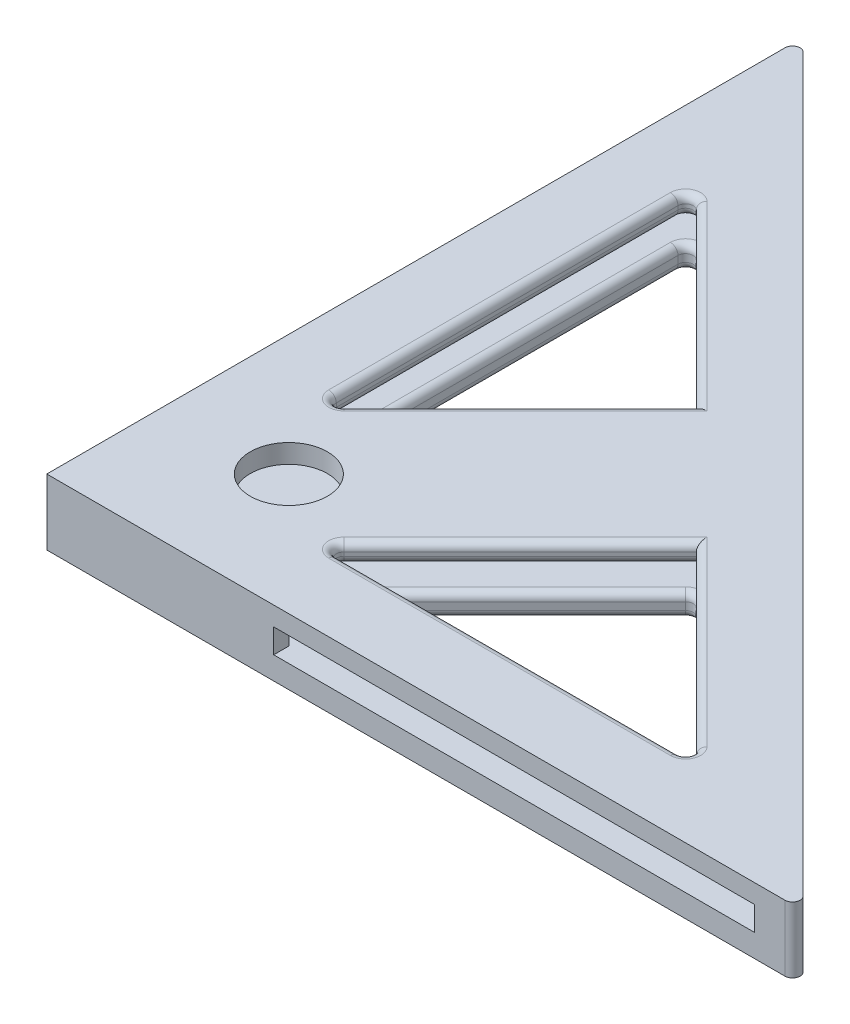
SolidWorks part; units mm, degrees
ref_plane "Front Plane" through (0, 0, 0) normal (0, 0, 1) x (1, 0, 0)
ref_plane "Top Plane" through (0, 0, 0) normal (0, 1, 0) x (1, 0, 0)
ref_plane "Right Plane" through (0, 0, 0) normal (1, 0, 0) x (0, 0, -1)
sketch "Sketch1" plane through (0, 0, 0) normal (0, 1, 0) x (1, 0, 0)
  line L0 (0, 0) -> (0, 28)
  line L1 (0, 28) -> (28, 0)
  line L2 (28, 0) -> (0, 0)
  circle A0 centre (14, 14) radius 5.1
  circle A1 centre (14, 14) radius 6.6
  dimension "D1" = 14
  dimension "D3" = 10.2
  dimension "D4" = 13.2
  dimension "D2" = 14
extrude "Boss-Extrude1" add sketch "Sketch1" along normal blind 3.1 contours L1 A1 A0 | L1 A1 A0
sketch "Sketch2" plane through (0, 3.1, 0) normal (0, 1, 0) x (1, 0, 0)
  line L0 (0, 0) -> (0, 28)
  line L1 (0, 28) -> (28, 0)
  line L2 (28, 0) -> (0, 0)
  line L3 (0, 28) -> (16.8443, 19.9557)
  line L4 (28, 0) -> (19.9557, 16.8443)
  line L5 (21.4946, 8.981) -> (23.8734, 4)
  line L6 (23.8734, 4) -> (18.6188, 4)
  line L7 (18.6188, 4) -> (21.4946, 8.981)
  line L8 (0, 0) -> (18.6669, 18.6669) construction
  line L9 (4, 23.8734) -> (4, 18.6188)
  line L10 (8.981, 21.4946) -> (4, 23.8734)
  line L11 (4, 18.6188) -> (8.981, 21.4946)
  circle A0 centre (14, 14) radius 6.6
  circle M11 centre (14, 14) radius 5.1
  circle M12 centre (14, 14) radius 6.6
  dimension "D1" = 13.2
  dimension "D2" = 2
  dimension "D3" = 4
  dimension "D4" = 9
  dimension "D5" = 60
extrude "Boss-Extrude2" add sketch "Sketch2" along normal blind 3 contours L11 L1 L3 L10 M12 | L0 L8 L1 L11 L9 L10 M12 | L8 L2 L1 L5 L6 L7 A0 | L1 L7 L5 L4 M12 | L8 L1 M11 M12 | L8 A0 L1 M11 M12 | L8 L1 M11 | L1 L8 M11 | L8 L1 M11 | L8 L1 M11 | L8 L1 M12 M11 | L8 A0 L1 M11
sketch "Sketch4" plane through (0, 6.1, 0) normal (0, 1, 0) x (1, 0, 0)
  line L0 (0, 28) -> (-2, 28)
  line L1 (-2, 28) -> (-2, -2)
  line L2 (-2, -2) -> (28, -2)
  line L3 (28, -2) -> (28, 0)
  line L4 (28, 0) -> (0, 0) construction
  line L5 (0, 0) -> (0, 28) construction
  line L10 (28, 0) -> (19.9557, 16.8443)
  line L11 (16.8443, 19.9557) -> (0, 28)
  line L12 (0, 28) -> (0, 0)
  line L13 (0, 0) -> (28, 0)
  line L16 (0, 28) -> (0, 0)
  line L17 (0, 0) -> (28, 0)
  arc A1 (19.9557, 16.8443) -> (16.8443, 19.9557) centre (14, 14) ccw
  dimension "D1" = 2
  dimension "D2" = 2
  dimension "D3" = 0
extrude "Boss-Extrude4" add sketch "Sketch4" against normal blind 3 and the other way blind 3.2
sketch "Sketch5" plane through (0, 9.3, 0) normal (0, 1, 0) x (1, 0, 0)
  line L0 (-2, 28) -> (0, 28)
  line L1 (0, 28) -> (15.6957, 20.5042)
  line L2 (20.5042, 15.6957) -> (28, 0)
  line L3 (28, 0) -> (28, -2)
  line L4 (28, -2) -> (-2, -2)
  line L5 (-2, -2) -> (-2, 28)
  line L6 (28, 0) -> (19.9557, 16.8443) construction
  line L7 (0, 28) -> (16.8443, 19.9557) construction
  arc A0 (15.6957, 20.5042) -> (20.5042, 15.6957) centre (11.3, 11.3) cw
  dimension "D1" = 10.2
extrude "Boss-Extrude5" add sketch "Sketch5" along normal blind 2.5
sketch "Sketch6" plane through (0, 11.8, 0) normal (0, 1, 0) x (1, 0, 0)
  line L0 (-2, -2) -> (-2, 98)
  line L1 (-2, 98) -> (98, -2)
  line L2 (98, -2) -> (-2, -2)
  line L3 (-2, -2) -> (28, -2) construction
  dimension "D1" = 100
  dimension "D2" = 100
extrude "Boss-Extrude6" add sketch "Sketch6" against normal up to surface (2.5 mm away) up to face at (12.9225, 9.3, -12.9225)
sketch "Sketch7" plane through (0, 3.1, 0) normal (0, -1, 0) x (1, 0, 0)
  circle A0 centre (14, -14) radius 5.1
extrude "Cut-Extrude1" cut sketch "Sketch7" against normal blind 10 from surface at -3 starting at face at (13.0134, 6.1, -13.0134)
sketch "Sketch18" plane through (0, 3.1, 0) normal (0, -1, 0) x (1, 0, 0)
  line L0 (-2, 2) -> (98, 2)
  line L1 (98, 2) -> (-2, -98)
  line L2 (-2, -98) -> (-2, 2)
  line L3 (-2, -28) -> (-2, 2) construction
  dimension "D1" = 100
  dimension "D2" = 100
extrude "Boss-Extrude7" add sketch "Sketch18" against normal up to surface (3 mm away) up to face at (13.0134, 6.1, -13.0134)
fillet "Fillet1" radius 1 4 edges at (98, 10.55, 2) (98, 4.6, 2) (-2, 4.6, -98) (-2, 10.55, -98)
sketch "Sketch19" plane through (0, 3.1, 0) normal (0, -1, 0) x (1, 0, 0)
  line L0 (33, -48.8579) -> (8, -73.8579)
  line L1 (8, -73.8579) -> (8, -23.8579)
  line L2 (8, -23.8579) -> (33, -48.8579)
  line L3 (-0.2929, -96.2929) -> (96.2929, 0.2929) construction
  line L4 (-2, -95.5858) -> (-2, 2) construction
  dimension "D1" = 10
  dimension "D2" = 10
  dimension "D3" = 50
extrude "Cut-Extrude3" cut sketch "Sketch19" against normal through all
fillet "Fillet2" radius 1 17 edges at (20.5, 6.1, -61.3579) (20.5, 3.1, -61.3579) (20.5, 3.1, -36.3579) (20.5, 6.1, -36.3579) (20.5, 11.8, -36.3579) (20.5, 11.8, -61.3579) (20.5, 9.3, -61.3579) (20.5, 9.3, -36.3579) (8, 4.6, -73.8579) (8, 3.1, -48.8579) (8, 4.6, -23.8579) (8, 6.1, -48.8579) (8, 11.8, -48.8579) (8, 10.55, -73.8579) (8, 9.3, -48.8579) (8, 10.55, -23.8579) (33, 4.6, -48.8579)
ref_plane "Plane2" through (0, 0, 0) normal (-0.7071, 0, -0.7071) x (-0.7071, 0, 0.7071)
mirror "Mirror1" about plane through (0, 0, 0) normal (-0.7071, 0, -0.7071) of "Cut-Extrude3", "Fillet2"
sketch "Sketch20" plane through (-2, 0, 0) normal (-1, 0, 0) x (0, 0, 1)
  line L0 (-28, 6.1) -> (-95.5858, 6.1) construction
  line L1 (-95.5858, 9.3) -> (-91.5858, 9.3)
  line L2 (-95.5858, 9.3) -> (-95.5858, 6.1)
  line L3 (-95.5858, 6.1) -> (-91.5858, 6.1)
  line L4 (-91.5858, 9.3) -> (-91.5858, 6.1)
  dimension "D1" = 4
extrude "Boss-Extrude8" add sketch "Sketch20" against normal up to surface (2 mm away) up to face at (0, 7.7, -14)
sketch "Sketch21" plane through (0, 6.1, 0) normal (0, 1, 0) x (1, 0, 0)
  line L0 (0, 95.5858) -> (0, 96)
  line L1 (-0.2929, 96.2929) -> (96.2929, -0.2929) construction
  line L2 (0, 96) -> (-0.2929, 96.2929)
  line L13 (-2, 95.5858) -> (0, 95.5858)
  line L14 (0, 95.5858) -> (0, 91.5858)
  line L15 (0, 91.5858) -> (-2, 91.5858)
  line L16 (-2, 91.5858) -> (-2, 28)
  line L17 (-2, 28) -> (0, 28)
  line L18 (0, 28) -> (0, 0)
  line L19 (0, 0) -> (28, 0)
  line L20 (28, 0) -> (28, -2)
  line L21 (28, -2) -> (95.5858, -2)
  line L22 (96.2929, -0.2929) -> (-0.2929, 96.2929)
  line L24 (0, 95.5858) -> (0, 91.5858)
  line L25 (0, 91.5858) -> (-2, 91.5858)
  line L26 (-2, 91.5858) -> (-2, 28)
  line L27 (-2, 28) -> (0, 28)
  line L28 (0, 28) -> (0, 0)
  line L29 (0, 0) -> (28, 0)
  line L30 (28, 0) -> (28, -2)
  line L31 (28, -2) -> (95.5858, -2)
  line L32 (96.2929, -0.2929) -> (-0.2929, 96.2929)
  arc A2 (95.5858, -2) -> (96.2929, -0.2929) centre (95.5858, -1) ccw
  arc A3 (-0.2929, 96.2929) -> (-2, 95.5858) centre (-1, 95.5858) ccw
  arc A4 (95.5858, -2) -> (96.2929, -0.2929) centre (95.5858, -1) ccw
  line M13 (-2, 95.5858) -> (0, 95.5858)
  line M23 (96.2929, -0.2929) -> (-0.2929, 96.2929)
  arc M24 (-0.2929, 96.2929) -> (-2, 95.5858) centre (-1, 95.5858) ccw
  dimension "D1" = 0
extrude "Boss-Extrude9" add sketch "Sketch21" along direction (0, -1, 0) on the side of the normal up to surface (3.2 mm away) contours L0 M13 M23 M24
sketch "Sketch22" plane through (0, 0, 2) normal (0, 0, 1) x (1, 0, 0)
  line L0 (28, 9.3) -> (95.5858, 9.3) construction
  line L1 (95.5858, 6.1) -> (91.5858, 6.1)
  line L2 (95.5858, 6.1) -> (95.5858, 9.3)
  line L3 (95.5858, 9.3) -> (91.5858, 9.3)
  line L4 (91.5858, 6.1) -> (91.5858, 9.3)
  dimension "D1" = 4
extrude "Boss-Extrude10" add sketch "Sketch22" against normal up to surface (2 mm away) up to face at (14, 7.7, 0)
sketch "Sketch23" plane through (0, 6.1, 0) normal (0, 1, 0) x (1, 0, 0)
  line L0 (95.5858, 0) -> (96, 0)
  line L1 (0, 96) -> (96.2929, -0.2929) construction
  line L2 (96, 0) -> (96.2929, -0.2929)
  line L15 (95.5858, 0) -> (95.5858, -2)
  line L16 (96.2929, -0.2929) -> (0, 96)
  line L17 (0, 96) -> (0, 91.5858)
  line L18 (0, 91.5858) -> (-2, 91.5858)
  line L19 (-2, 91.5858) -> (-2, 28)
  line L20 (-2, 28) -> (0, 28)
  line L21 (0, 28) -> (0, 0)
  line L22 (0, 0) -> (28, 0)
  line L23 (28, 0) -> (28, -2)
  line L24 (28, -2) -> (91.5858, -2)
  line L25 (91.5858, -2) -> (91.5858, 0)
  line L26 (91.5858, 0) -> (95.5858, 0)
  line L27 (95.5858, 0) -> (95.5858, -2)
  arc A1 (95.5858, -2) -> (96.2929, -0.2929) centre (95.5858, -1) ccw
  arc A2 (95.5858, -2) -> (96.2929, -0.2929) centre (95.5858, -1) ccw
  dimension "D1" = 0
extrude "Boss-Extrude11" add sketch "Sketch23" along normal up to surface (3.2 mm away) up to face at (40.2466, 9.3, -25.2802)
